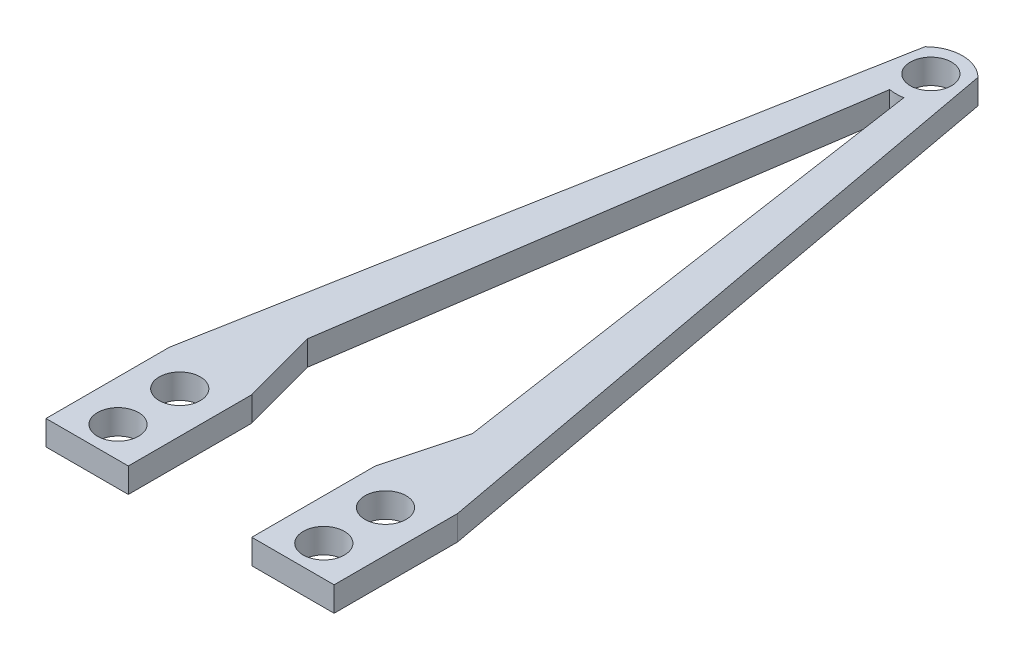
SolidWorks part; units mm, degrees
ref_plane "Front Plane" through (0, 0, 0) normal (0, 0, 1) x (1, 0, 0)
ref_plane "Top Plane" through (0, 0, 0) normal (0, 1, 0) x (1, 0, 0)
ref_plane "Right Plane" through (0, 0, 0) normal (1, 0, 0) x (0, 0, -1)
sketch "Sketch1" plane through (0, 0, 0) normal (0, 1, 0) x (1, 0, 0)
  line L0 (0, 15) -> (0, 205) construction
  line L1 (-35, -15) -> (35, -15)
  line L2 (-35, -15) -> (-35, 15)
  line L4 (35, -15) -> (35, 15)
  line L5 (-35, -15) -> (35, 15) construction
  line L6 (-35, 15) -> (35, -15) construction
  line L10 (-35, 15) -> (35, 15) construction
  line L11 (-35, 15) -> (-6.4474, 170)
  line L12 (6.4474, 170) -> (35, 15)
  line L13 (0, 15) -> (0, 165) construction
  line L16 (0, 15) -> (0, -15) construction
  circle A0 centre (0, 165) radius 5
  arc A1 (-6.4474, 170) -> (6.4474, 170) centre (0, 163.5526) cw
  circle A2 centre (-25, 7.5) radius 5
  circle A3 centre (-25, -7.5) radius 5
  circle A4 centre (25, 7.5) radius 5
  circle A5 centre (25, -7.5) radius 5
  point P0 (0, 0)
  point P13 (0, 0)
  point P17 (0, 0)
  point P20 (-25, 0)
  point P25 (0, 172.6706)
  dimension "D4" = 15
  dimension "D3" = 50
  dimension "D1" = 70
  dimension "D2" = 30
extrude "Boss-Extrude1" add sketch "Sketch1" along normal blind 6
sketch "Sketch6" plane through (0, 6, 0) normal (0, 1, 0) x (1, 0, 0)
  line L0 (-30, -7.5) -> (-35, -7.5) construction
  line L1 (-35, 15) -> (-35, -15) construction
  line L2 (-20, -7.5) -> (-15, -7.5) construction
  line L3 (-35, 15) -> (35, 15) construction
  line L4 (-15, -15) -> (-15, 15)
  line L5 (-35, -15) -> (35, -15) construction
  line L6 (20, -7.5) -> (15, -7.5) construction
  line L7 (15, -15) -> (15, 15)
  line L10 (-15, -15) -> (15, -15)
  line L11 (-15, 15) -> (-20, 33.5951)
  line L12 (15, 15) -> (20, 33.5951)
  line L15 (-20, 33.5951) -> (-1.7218, 156.6935)
  line L16 (20, 33.5951) -> (1.7218, 156.6935)
  circle A0 centre (-25, -7.5) radius 5 construction
  circle A1 centre (25, -7.5) radius 5 construction
  arc A2 (-1.7218, 156.6935) -> (1.7218, 156.6935) centre (0, 168.2895) ccw
extrude "Cut-Extrude1" cut sketch "Sketch6" against normal blind 10
